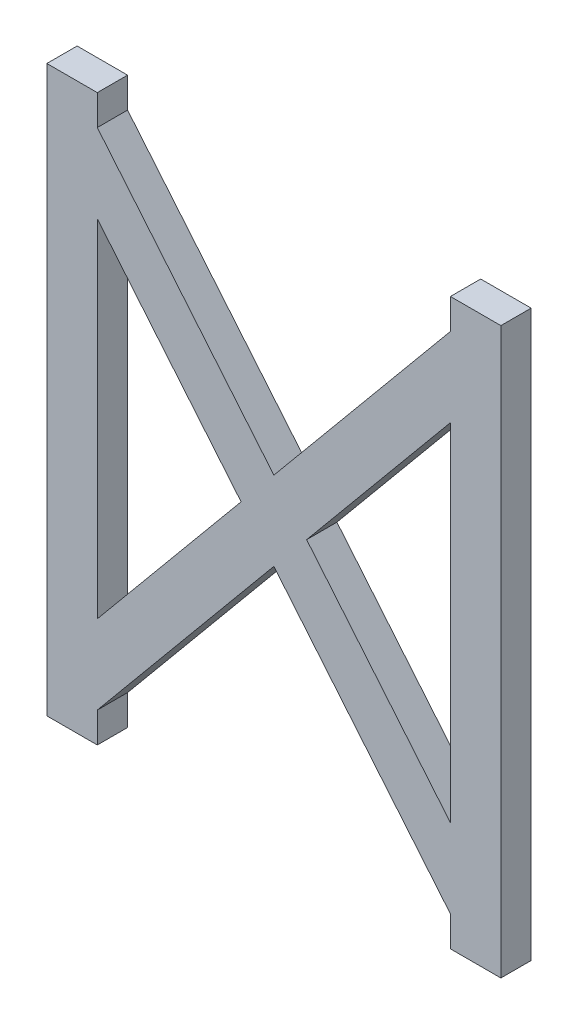
SolidWorks part; units mm, degrees
ref_plane "Alzado" through (0, 0, 0) normal (0, 0, 1) x (1, 0, 0)
ref_plane "Planta" through (0, 0, 0) normal (0, 1, 0) x (1, 0, 0)
ref_plane "Vista lateral" through (0, 0, 0) normal (1, 0, 0) x (0, 0, -1)
sketch "Sketch1" plane through (0, 0, 0) normal (0, 0, 1) x (1, 0, 0)
  line L0 (0, 0) -> (0, 56)
  line L1 (0, 56) -> (5, 56)
  line L2 (5, 56) -> (5, 0)
  line L3 (5, 0) -> (0, 0)
  line L4 (40, 56) -> (45, 56)
  line L5 (40, 0) -> (40, 56)
  line L6 (45, 56) -> (45, 0)
  line L7 (45, 0) -> (40, 0)
  line L8 (5, 53) -> (40, 10.829)
  line L9 (5, 45.171) -> (40, 3)
  line L10 (0, 28) -> (45, 28) construction
  line L11 (5, 10.829) -> (40, 53)
  line L12 (5, 3) -> (40, 45.171)
  dimension "D1" = 5
  dimension "D2" = 56
  dimension "D4" = 3
  dimension "D5" = 3
  dimension "D6" = 5
  dimension "D7" = 45
  dimension "D3" = 2
extrude "Boss-Extrude1" add sketch "Sketch1" along normal blind 3 contours L0 L10 L2 L1 | L9 L11 L8 L2 | L10 L0 L3 L2 | L2 L12 L9 L11 | L10 L9 L12 | L8 L12 L5 L11 | L5 L10 L6 L4 | L10 L5 L7 L6 | L12 L9 L5 L8 | L11 L10 L8
